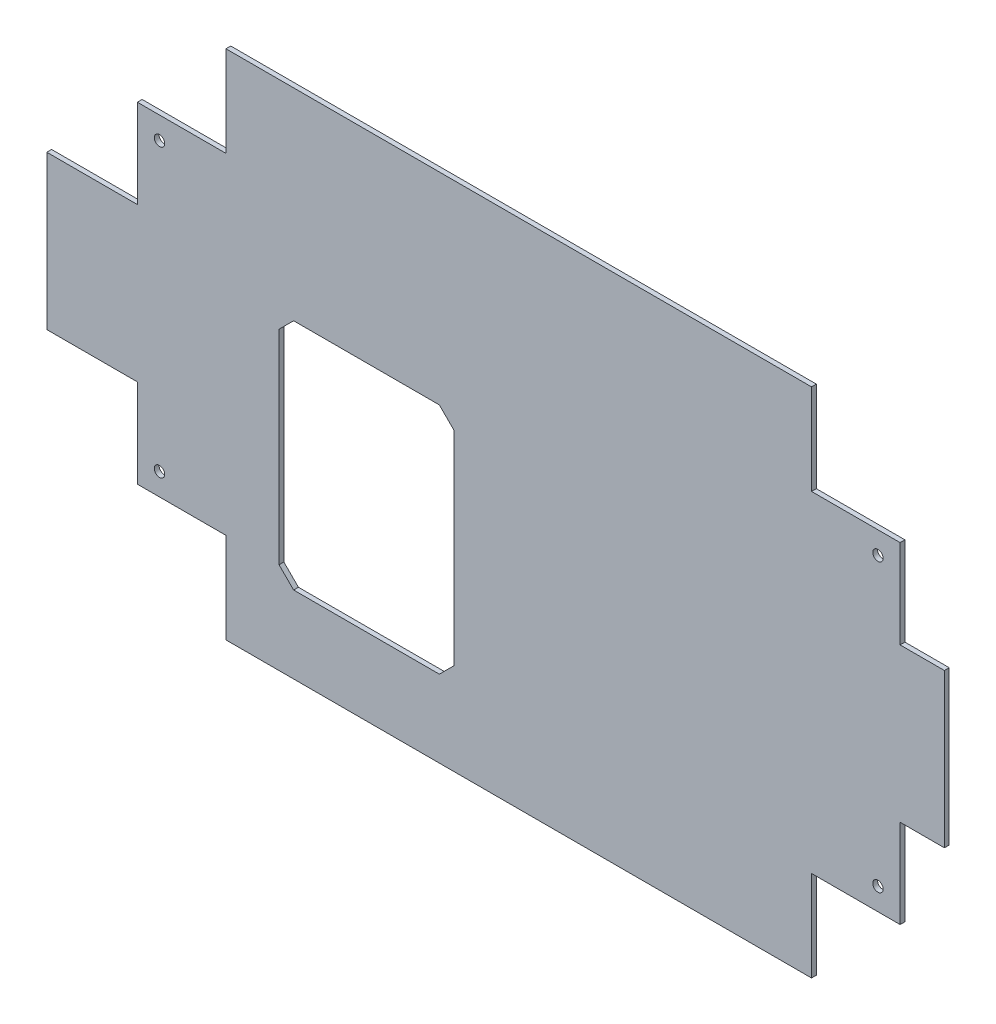
SolidWorks part; units mm, degrees
ref_plane "Plan de face" through (0, 0, 0) normal (0, 0, 1) x (1, 0, 0)
ref_plane "Plan de dessus" through (0, 0, 0) normal (0, 1, 0) x (1, 0, 0)
ref_plane "Plan de droite" through (0, 0, 0) normal (1, 0, 0) x (0, 0, -1)
sketch "Esquisse1" plane through (0, 0, 0) normal (0, 0, 1) x (1, 0, 0)
  line L0 (-615.95, 52.7) -> (-615.95, -52.7)
  line L1 (-615.95, -52.7) -> (-553.8, -52.7)
  line L2 (-553.8, -52.7) -> (-553.8, -113.5)
  line L3 (-553.8, -113.5) -> (-493, -113.5)
  line L4 (-493, -113.5) -> (-493, -174.3)
  line L5 (-493, -174.3) -> (-91.2, -174.3)
  line L6 (-91.2, -174.3) -> (-91.2, -113.5)
  line L7 (-91.2, -113.5) -> (-30.4, -113.5)
  line L8 (-30.4, -113.5) -> (-30.4, -52.7)
  line L9 (-30.4, -52.7) -> (0, -52.7)
  line L10 (0, -52.7) -> (0, 52.7)
  line L11 (0, 52.7) -> (-30.4, 52.7)
  line L12 (-30.4, 52.7) -> (-30.4, 113.5)
  line L13 (-30.4, 113.5) -> (-91.2, 113.5)
  line L14 (-91.2, 113.5) -> (-91.2, 182)
  line L15 (-615.95, 52.7) -> (-553.8, 52.7)
  line L16 (-553.8, 52.7) -> (-553.8, 113.5)
  line L17 (-553.8, 113.5) -> (-493, 113.5)
  line L18 (-493, 113.5) -> (-493, 182)
  line L19 (-493, 182) -> (-91.2, 182)
  point P28 (0, 0)
  dimension "D1" = 105.4
  dimension "D2" = 401.8
  dimension "D3" = 60.8
  dimension "D4" = 30.4
  dimension "D5" = 60.8
  dimension "D6" = 68.5
  dimension "D7" = 60.8
  dimension "D8" = 60.8
  dimension "D9" = 62.15
extrude "Boss.-Extru.1" add sketch "Esquisse1" along normal blind 3.3
sketch "Esquisse2" plane through (0, 0, 3.3) normal (0, 0, 1) x (1, 0, 0)
  line L0 (-91.2, 113.5) -> (-91.2, 182) construction
  line L1 (-493, 182) -> (-91.2, 182)
  line L2 (-493, 182) -> (-493, 175.65)
  line L3 (-493, 175.65) -> (-91.2, 175.65)
  line L4 (-91.2, 182) -> (-91.2, 175.65)
  line L5 (-493, 182) -> (-91.2, 175.65) construction
  line L6 (-493, 175.65) -> (-91.2, 182) construction
  line L7 (-91.2, 182) -> (-493, 182) construction
  line L8 (-493, 182) -> (-493, 113.5) construction
  point P4 (-292.1, 178.825)
  dimension "D1" = 6.35
extrude "Enlèv. mat.-Extru.1" cut sketch "Esquisse2" against normal through all
hole_wizard "Dégagement 1/41" positions "Esquisse3" profile "Esquisse4" hole size "1/4" standard "Ansi Inch" end condition through all
sketch "Esquisse3" plane through (0, 0, 0) normal (0, 0, -1) x (-1, 0, 0)
  point P0 (45.6, 98.3)
  point P2 (45.6, -98.3)
  point P4 (538.6, -98.3)
  point P6 (538.6, 98.3)
sketch "Esquisse4" plane through (-45.6, 98.3, 0) normal (1, 0, 0) x (0, 1, 0)
  line L0 (0, 0) -> (0, 3.3)
  line L1 (0, 3.3) -> (3.5712, 3.3)
  line L2 (3.5712, 3.3) -> (3.5712, 0)
  line L5 (3.5712, 0) -> (0, 0)
  line L11 (0, -6.35) -> (0, 107.95) construction
  dimension "Diamètre du perçage jusqu'au prochain" = 7.1425
  dimension "Profondeur du perçage jusqu'au prochain" = 3.3
sketch "Esquisse5" plane through (0, 0, 3.3) normal (0, 0, 1) x (1, 0, 0)
  line L0 (-91.2, -174.3) -> (-91.2, -113.5) construction
  line L1 (-493, -174.3) -> (-91.2, -174.3)
  line L2 (-493, -174.3) -> (-493, -175.65)
  line L3 (-493, -175.65) -> (-91.2, -175.65)
  line L4 (-91.2, -174.3) -> (-91.2, -175.65)
  line L5 (-493, -174.3) -> (-91.2, -175.65) construction
  line L6 (-493, -175.65) -> (-91.2, -174.3) construction
  point P4 (-292.1, -174.975)
  dimension "D1" = 1.35
extrude "Boss.-Extru.2" add sketch "Esquisse5" against normal through all
mirror "Symétrie1" [suppressed]
delete or keep bodies "Corps-Supprimer/Garder 1" [suppressed] type delete bodies bodies 105
sketch "Esquisse6" plane through (0, 0, 0) normal (0, 0, -1) x (-1, 0, 0)
  line L0 (336.5665, -122.7684) -> (456.5665, -122.7684)
  line L1 (456.5665, -122.7684) -> (456.5665, 37.2316)
  line L2 (456.5665, 37.2316) -> (336.5665, 37.2316)
  line L3 (336.5665, 37.2316) -> (336.5665, -122.7684)
  line L4 (396.5665, 37.2316) -> (396.5665, -122.7684) construction
  line L5 (456.5665, -42.7684) -> (336.5665, -42.7684) construction
  point P8 (396.5665, -42.7684)
  dimension "D1" = 120
  dimension "D2" = 160
  dimension "D3" = 396.5665
  dimension "D4" = 42.7684
extrude "Enlèv. mat.-Extru.2" cut sketch "Esquisse6" against normal through all
chamfer "Chanfrein1" distance 10 angle 45 4 edges at (-336.5665, -122.7684, 1.65) (-456.5665, -122.7684, 1.65) (-456.5665, 37.2316, 1.65) (-336.5665, 37.2316, 1.65)
